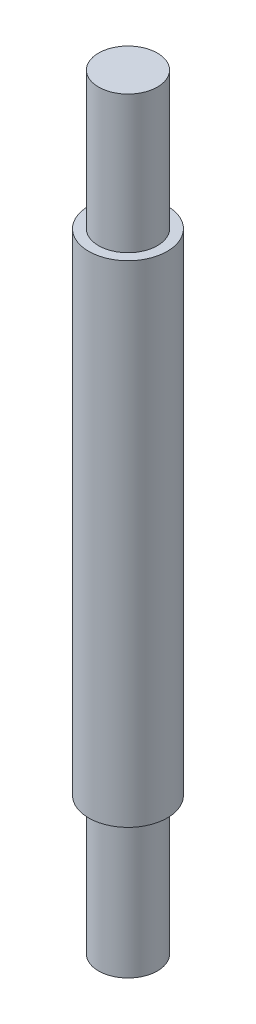
SolidWorks part; units mm, degrees
material "Brass"
ref_plane "Front Plane" through (0, 0, 0) normal (0, 0, 1) x (1, 0, 0)
ref_plane "Top Plane" through (0, 0, 0) normal (0, 1, 0) x (1, 0, 0)
ref_plane "Right Plane" through (0, 0, 0) normal (1, 0, 0) x (0, 0, -1)
sketch "Sketch1" plane through (0, 0, 0) normal (0, 1, 0) x (1, 0, 0)
  circle A0 centre (0, 0) radius 2
  dimension "D1" = 4
extrude "Boss-Extrude1" add sketch "Sketch1" along normal blind 25
sketch "Sketch2" plane through (0, 25, 0) normal (0, 1, 0) x (1, 0, 0)
  circle A0 centre (0, 0) radius 1.5
  dimension "D1" = 3
extrude "Boss-Extrude2" add sketch "Sketch2" along normal blind 7
sketch "Sketch3" plane through (0, 0, 0) normal (0, -1, 0) x (1, 0, 0)
  circle A0 centre (0, 0) radius 1.5
  dimension "D1" = 3
extrude "Boss-Extrude3" add sketch "Sketch3" along normal blind 7
